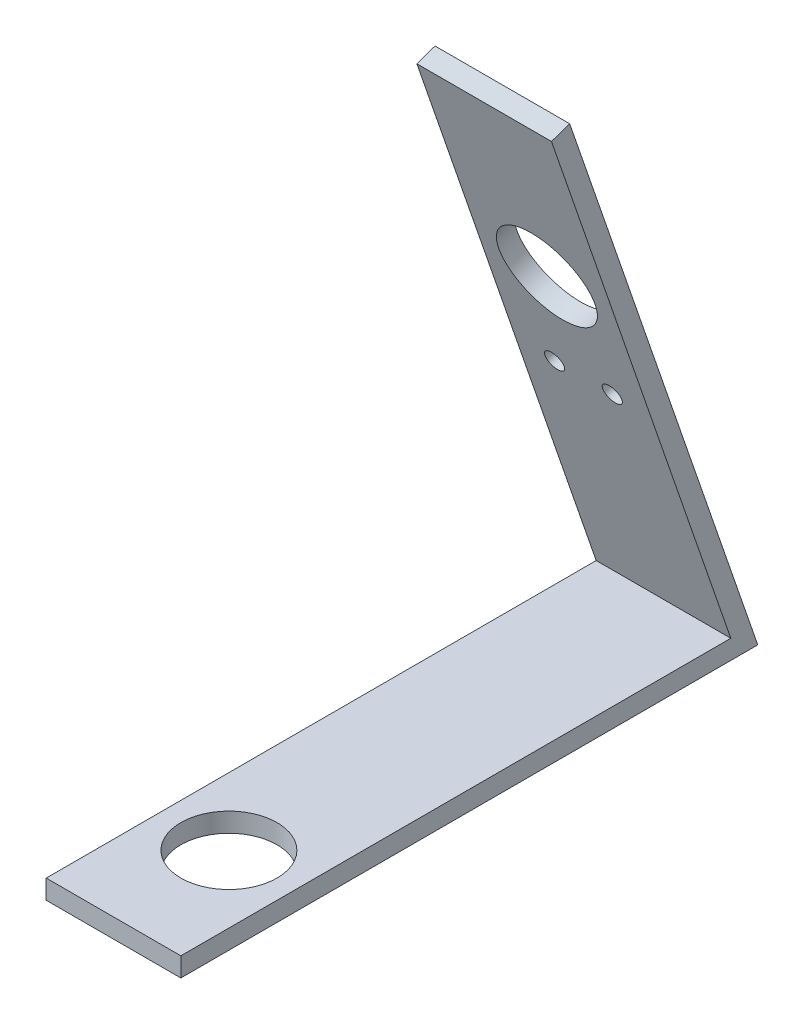
SolidWorks part; units mm, degrees
ref_plane "Front Plane" through (0, 0, 0) normal (0, 0, 1) x (1, 0, 0)
ref_plane "Top Plane" through (0, 0, 0) normal (0, 1, 0) x (1, 0, 0)
ref_plane "Right Plane" through (0, 0, 0) normal (1, 0, 0) x (0, 0, -1)
sketch "Sketch1" plane through (0, 0, 0) normal (1, 0, 0) x (0, 0, -1)
  line L0 (-93.2452, 270.3438) -> (0, 0)
  line L1 (0, 0) -> (-285.9728, 0)
  line L2 (-285.9728, 0) -> (-285.9728, -10)
  line L3 (-285.9728, -10) -> (14.0272, -10)
  line L4 (14.0272, -10) -> (-83.7917, 273.6044)
  line L5 (-83.7917, 273.6044) -> (-93.2452, 270.3438)
  dimension "D1" = 10
  dimension "D2" = 10
  dimension "D3" = 300
  dimension "D4" = 300
  dimension "D5" = 70.97
extrude "Boss-Extrude1" add sketch "Sketch1" along normal blind 70
sketch "Sketch2" plane through (0, 3.2606, -9.4535) normal (0, 0.3261, -0.9453) x (1, 0, 0)
  line L0 (0, 14.0272) -> (0, -285.9728) construction
  line L4 (70, -285.9728) -> (0, -285.9728) construction
  circle A0 centre (35, -185.9728) radius 25
  dimension "D1" = 50
  dimension "D2" = 35
  dimension "D3" = 100
extrude "Cut-Extrude1" cut sketch "Sketch2" against normal blind 10
sketch "Sketch5" plane through (0, 0, 0) normal (0, 1, 0) x (1, 0, 0)
  line L0 (70, -285.9728) -> (0, -285.9728) construction
  line L1 (70, 14.0272) -> (70, -83.7917) construction
  circle A0 centre (35, -225.9728) radius 25
  dimension "D1" = 50
  dimension "D2" = 60
  dimension "D3" = 35
extrude "Cut-Extrude3" cut sketch "Sketch5" against normal blind 300
sketch "Sketch6" plane through (0, 3.2606, -9.4535) normal (0, 0.3261, -0.9453) x (1, 0, 0)
  line L5 (70, 14.0272) -> (70, -285.9728) construction
  line L6 (0, 14.0272) -> (0, -285.9728) construction
  circle A0 centre (50, -197.6795) radius 5
  circle A1 centre (20, -197.6795) radius 5
  circle A2 centre (20, -127.6795) radius 5
  circle A3 centre (50, -127.6795) radius 5
  point P0 (35, -185.9728)
  dimension "D2" = 10
  dimension "D3" = 10
  dimension "D4" = 10
  dimension "D5" = 10
  dimension "D1" = 20
  dimension "D6" = 20
  dimension "D7" = 20
  dimension "D8" = 20
extrude "Cut-Extrude5" cut sketch "Sketch6" against normal blind 10
equation "\"mountAngle\"=70.9702deg"
equation "\"D5@Sketch1\"=\"mountAngle\""
equation "\"ThrusterDim\"=160.5mm"
equation "\"hatchHoleDiameter\"=600mm"
equation "\"hullThickness\"=177.1mm"
equation "\"gasketHullInterconnectWidth\"=100mm"
equation "\"collarThickness\"=20mm"
equation "\"hatchTunnelLength\"=200mm"
equation "\"oRingDiameter\"=2mm"
equation "\"boltPatternRadiusInterconnect\"=500mm"
equation "\"interconnectBoltDiameter\"=30mm"
equation "\"hatchShaftDiameter\"=20mm"
equation "\"hatchMinima\"=39.9mm"
equation "\"hullDiameter\"=2240mm"
equation "\"hatchMaxima\"=180mm"
equation "\"bushingFlatHatch\"=15mm"
equation "\"hingePivotDiameter\"=20mm"
equation "\"handleWidth\"=250mm"
equation "\"handleHeight\"=160mm"
equation "\"handleThickness\"=25mm"
equation "\"FrameLength\"=2600mm"
equation "\"FrameMidLength\"=1800mm"
equation "\"TubeOD\"=100mm"
equation "\"FrameBackFlat\"=500mm"
equation "\"TubeWall\"=15.0001mm"
equation "\"TopMemberAngle\"=140deg"
equation "\"FrameHight\"=2500mm"
